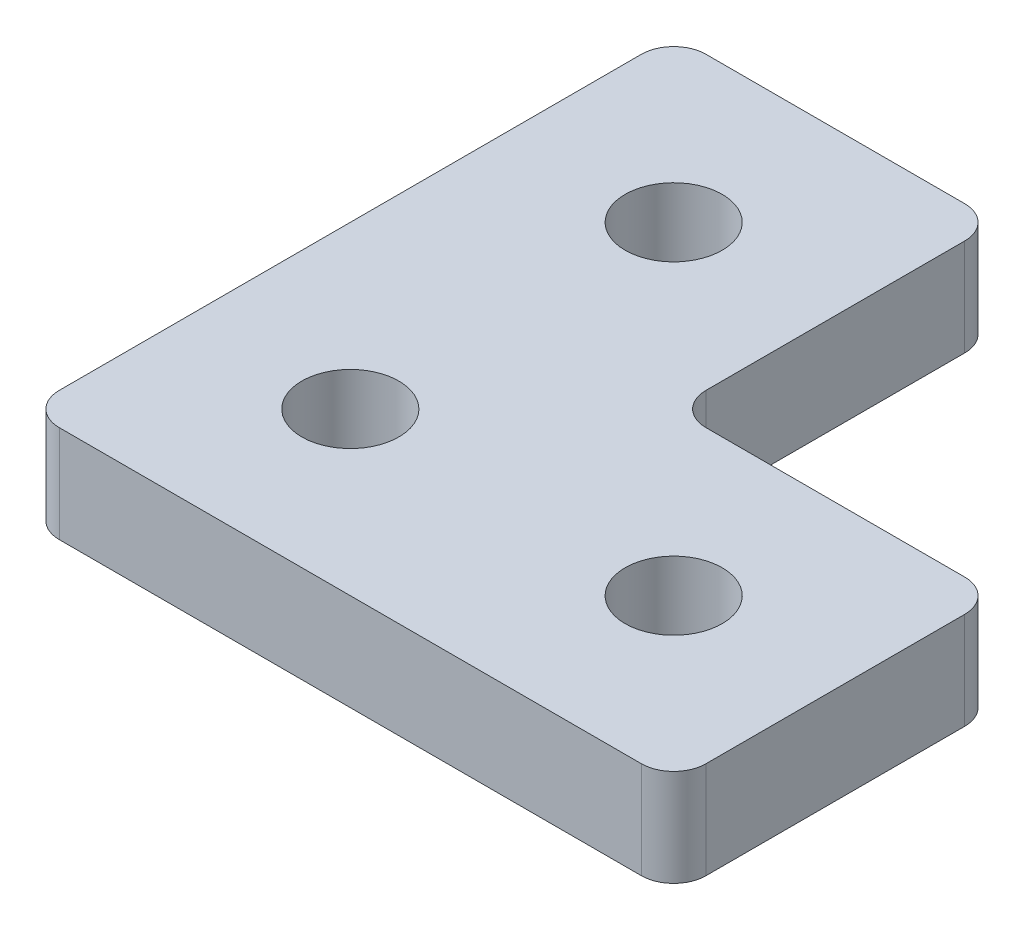
SolidWorks part; units mm, degrees
ref_plane "Front Plane" through (0, 0, 0) normal (0, 0, 1) x (1, 0, 0)
ref_plane "Top Plane" through (0, 0, 0) normal (0, 1, 0) x (1, 0, 0)
ref_plane "Right Plane" through (0, 0, 0) normal (1, 0, 0) x (0, 0, -1)
sketch "Sketch1" plane through (0, 0, 0) normal (0, 1, 0) x (1, 0, 0)
  line L0 (20, 5) -> (0, 5) construction
  line L1 (0, 0) -> (10, 0)
  line L2 (0, 0) -> (0, 20)
  line L3 (0, 20) -> (10, 20)
  line L4 (10, 10) -> (10, 20)
  line L5 (10, 0) -> (20, 0)
  line L7 (10, 10) -> (20, 10)
  line L8 (20, 0) -> (20, 10)
  line L9 (5, 20) -> (5, 0) construction
  line L10 (15, 10) -> (15, 0) construction
  circle A0 centre (5, 15) radius 1.5
  circle A1 centre (5, 5) radius 1.5
  circle A4 centre (5, -5) radius 1.5 [skipped]
  circle A5 centre (15, 5) radius 1.5
  point P10 (5, 20)
  dimension "D5" = 3
  dimension "D1" = 10
  dimension "D2" = 10
  dimension "D3" = 10
  dimension "D4" = 20
  dimension "D6" = 5
  dimension "D7" = 3
extrude "Boss-Extrude1" add sketch "Sketch1" along normal blind 3
fillet "Fillet1" radius 1 1 edges at (10, 1.5, -10)
fillet "Fillet2" radius 1 5 edges at (0, 1.5, -20) (10, 1.5, -20) (0, 1.5, 0) (20, 1.5, 0) (20, 1.5, -10)
